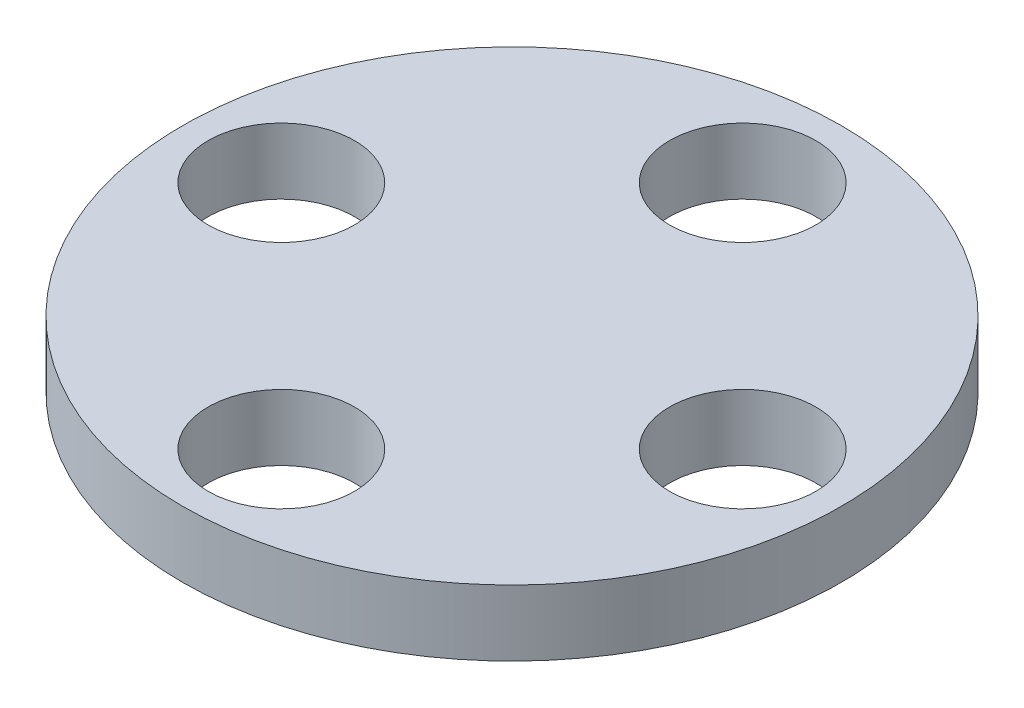
SolidWorks part; units mm, degrees
ref_plane "Front Plane" through (0, 0, 0) normal (0, 0, 1) x (1, 0, 0)
ref_plane "Top Plane" through (0, 0, 0) normal (0, 1, 0) x (1, 0, 0)
ref_plane "Right Plane" through (0, 0, 0) normal (1, 0, 0) x (0, 0, -1)
sketch "Sketch2" plane through (0, 0, 0) normal (0, 1, 0) x (1, 0, 0)
  line L0 (0, -0.7691) -> (0, 8.1209) construction
  circle A0 centre (0, -0.7691) radius 8.89 construction
  circle A1 centre (0, 8.1209) radius 2.8194
  circle A2 centre (8.89, -0.7691) radius 2.8194
  circle A3 centre (0, -9.6591) radius 2.8194
  circle A4 centre (-8.89, -0.7691) radius 2.8194
  circle A5 centre (0, -0.7691) radius 12.7
  dimension "D1" = 17.78
  dimension "D2" = 5.6388
  dimension "D5" = 25.4
  dimension "D4" = 8.89
  dimension "D3" = 4
extrude "Boss-Extrude1" add sketch "Sketch2" along normal blind 2.54
